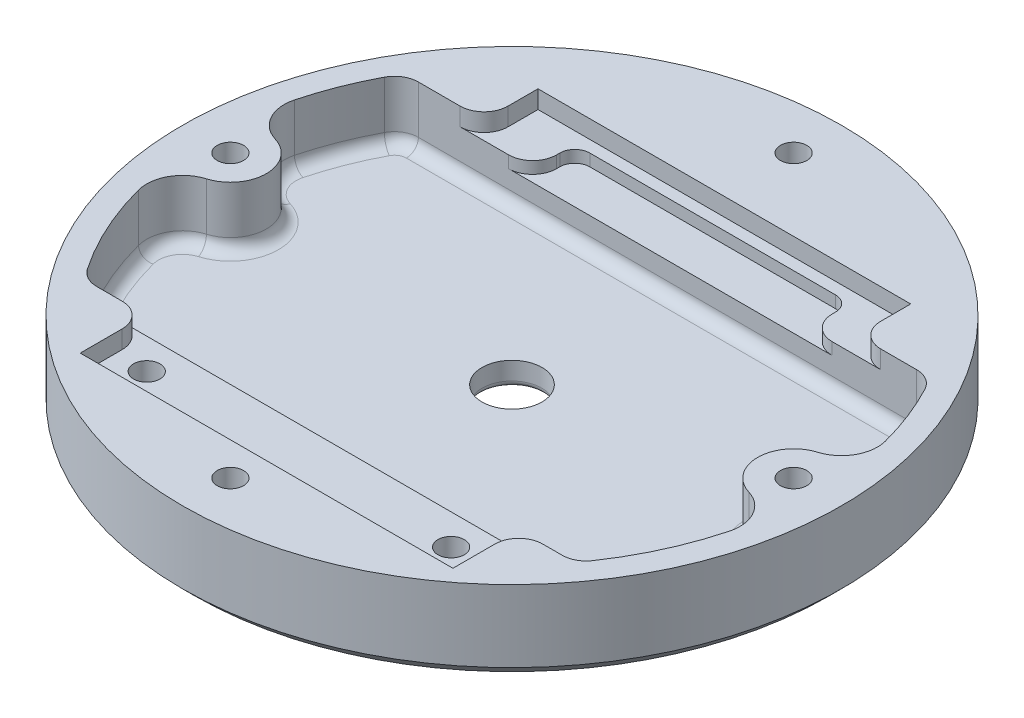
SolidWorks part; units mm, degrees
ref_plane "Спереди" through (0, 0, 0) normal (0, 0, 1) x (1, 0, 0)
ref_plane "Сверху" through (0, 0, 0) normal (0, 1, 0) x (1, 0, 0)
ref_plane "Справа" through (0, 0, 0) normal (1, 0, 0) x (0, 0, -1)
sketch "Эскиз1" plane through (0, 0, 0) normal (0, 1, 0) x (1, 0, 0)
  circle A0 centre (0, 0) radius 27.5
  dimension "D1" = 55
extrude "Бобышка-Вытянуть1" add sketch "Эскиз1" against normal blind 2
sketch "Эскиз2" plane through (0, 0, 0) normal (0, 1, 0) x (1, 0, 0)
  circle A0 centre (0, 0) radius 27.5
  circle A1 centre (0, 0) radius 25.5
  circle A2 centre (0, 0) radius 27.5 construction
  dimension "D1" = 2
extrude "Бобышка-Вытянуть2" add sketch "Эскиз2" along normal blind 5
sketch "Эскиз3" plane through (0, 0, 0) normal (0, 1, 0) x (1, 0, 0)
  line L0 (-21.9552, 12.97) -> (21.9552, 12.97)
  line L1 (15.05, -20.23) -> (-15.05, -20.23) construction
  line L2 (15.05, -20.23) -> (15.05, 16.97) construction
  line L3 (15.05, 16.97) -> (-15.05, 16.97) construction
  line L4 (-15.05, -20.23) -> (-15.05, 16.97) construction
  line L5 (15.05, -20.23) -> (-15.05, 16.97) construction
  line L6 (15.05, 16.97) -> (-15.05, -20.23) construction
  line L7 (-20.4523, -15.23) -> (20.4523, -15.23)
  circle A1 centre (0, 0) radius 25.5
  circle A2 centre (0, 0) radius 25.5 construction
  point P0 (0, -1.63)
  circle M5 centre (0, 0) radius 25.5
  dimension "D1" = 20.23
  dimension "D2" = 37.2
  dimension "D3" = 30.1
  dimension "D4" = 4
  dimension "D5" = 5
extrude "Бобышка-Вытянуть3" add sketch "Эскиз3" along normal up to surface (5 mm away) contours L0 M5 | L7 M5 up to face at (0, 5, 27.5)
sketch "Эскиз6" plane through (0, 5, 0) normal (0, 1, 0) x (1, 0, 0)
  line L1 (-15.3, 17.47) -> (15.8, 17.47)
  line L2 (-15.3, 17.47) -> (-15.3, -20.73)
  line L3 (-15.3, -20.73) -> (15.8, -20.73)
  line L4 (15.8, 17.47) -> (15.8, -20.73)
  line L5 (-15.3, 17.47) -> (15.8, -20.73) construction
  line L6 (-15.3, -20.73) -> (15.8, 17.47) construction
  point P0 (0.25, -1.63)
  point P5 (0, 0)
  dimension "D1" = 20.73
  dimension "D2" = 31.1
  dimension "D3" = 38.2
  dimension "D4" = 0.25
extrude "Вырез-Вытянуть1" cut sketch "Эскиз6" against normal blind 1.5
sketch "Эскиз7" plane through (0, 3.5, 0) normal (0, 1, 0) x (1, 0, 0)
  line L0 (-10, 15.24) -> (10.5, 15.24) construction
  line L1 (-10, 16.49) -> (10.5, 16.49)
  line L2 (-10, 13.99) -> (10.5, 13.99)
  line L3 (15.8, 17.47) -> (-15.3, 17.47) construction
  line L6 (0.25, 17.47) -> (0.25, 12.97) construction
  line L9 (-15.3, 12.97) -> (15.8, 12.97) construction
  line L12 (15.8, 17.47) -> (-15.3, 17.47) construction
  line L13 (-11.25, 15.24) -> (-11.25, 12.97)
  line L14 (-21.9552, 12.97) -> (21.9552, 12.97) construction
  line L15 (-11.25, 12.97) -> (11.75, 12.97)
  line L16 (11.75, 12.97) -> (11.75, 15.24)
  arc A0 (-10, 16.49) -> (-10, 13.99) centre (-10, 15.24) ccw
  arc A1 (10.5, 13.99) -> (10.5, 16.49) centre (10.5, 15.24) ccw
  point P2 (0.25, 15.24)
  line M7 (-15.3, 12.97) -> (15.8, 12.97)
  dimension "D1" = 2.5
  dimension "D2" = 23
  dimension "D3" = 2.23
extrude "Вырез-Вытянуть2" cut sketch "Эскиз7" against normal blind 1 contours L2 A1 L1 A0 | A1 L2 A0 L13 L16 M7
sketch "Эскиз8" plane through (0, 3.5, 0) normal (0, 1, 0) x (1, 0, 0)
  line L0 (0, 0) -> (0, -20.73) construction
  circle A0 centre (-12.7, -17.78) radius 1.1
  circle A1 centre (12.7, -17.78) radius 1.1
  dimension "D3" = 2.2
  dimension "D1" = 17.78
  dimension "D2" = 12.7
extrude "Вырез-Вытянуть3" cut sketch "Эскиз8" against normal through all
sketch "Эскиз9" plane through (0, 5, 0) normal (0, 1, 0) x (1, 0, 0)
  line L0 (0, 23.5) -> (0, -23.5) construction
  line L1 (-23.5, 3) -> (-25.3229, 3)
  line L2 (-23.5, -3) -> (-25.3229, -3)
  line L3 (23.5, 3) -> (25.3229, 3)
  line L4 (23.5, -3) -> (25.3229, -3)
  circle A0 centre (0, 0) radius 23.5 construction
  arc A1 (-23.5, -3) -> (-23.5, 3) centre (-23.5, 0) ccw
  arc A2 (-21.9552, 12.97) -> (-20.4523, -15.23) centre (0, 0) ccw construction
  arc A3 (-21.9552, 12.97) -> (-20.4523, -15.23) centre (0, 0) ccw construction
  arc A4 (-25.3229, -3) -> (-25.3229, 3) centre (0, 0) cw
  arc A5 (23.5, -3) -> (23.5, 3) centre (23.5, 0) cw
  arc A6 (25.3229, -3) -> (25.3229, 3) centre (0, 0) ccw
  point P18 (0, 0)
  dimension "D1" = 47
  dimension "D2" = 6
extrude "Бобышка-Вытянуть4" add sketch "Эскиз9" against normal through all
sketch "Эскиз10" plane through (0, 5, 0) normal (0, 1, 0) x (1, 0, 0)
  circle A0 centre (0, 0) radius 23.5 construction
  circle A1 centre (0, 23.5) radius 1.1
  circle A2 centre (23.5, 0) radius 1.1
  circle A3 centre (0, -23.5) radius 1.1
  circle A4 centre (-23.5, 0) radius 1.1
  point P5 (0, 0)
  point P6 (0, 0)
  dimension "D1" = 47
  dimension "D2" = 2.2
  dimension "D3" = 4
extrude "Вырез-Вытянуть4" cut sketch "Эскиз10" against normal through all
sketch "Эскиз11" plane through (0, -2, 0) normal (0, -1, 0) x (1, 0, 0)
  line L0 (0, 0) -> (0, 23.5) construction
  line L1 (1.1258, 21.55) -> (2.2517, 23.5)
  line L2 (2.2517, 23.5) -> (1.1258, 25.45)
  line L3 (1.1258, 25.45) -> (-1.1258, 25.45)
  line L4 (-1.1258, 25.45) -> (-2.2517, 23.5)
  line L5 (-2.2517, 23.5) -> (-1.1258, 21.55)
  line L6 (-1.1258, 21.55) -> (1.1258, 21.55)
  line L7 (13.8258, 15.83) -> (14.9517, 17.78)
  line L8 (14.9517, 17.78) -> (13.8258, 19.73)
  line L9 (13.8258, 19.73) -> (11.5742, 19.73)
  line L10 (11.5742, 19.73) -> (10.4483, 17.78)
  line L11 (10.4483, 17.78) -> (11.5742, 15.83)
  line L12 (11.5742, 15.83) -> (13.8258, 15.83)
  line L13 (-11.5742, 15.83) -> (-13.8258, 15.83)
  line L14 (-10.4483, 17.78) -> (-11.5742, 15.83)
  line L15 (-11.5742, 19.73) -> (-10.4483, 17.78)
  line L16 (-13.8258, 19.73) -> (-11.5742, 19.73)
  line L17 (-14.9517, 17.78) -> (-13.8258, 19.73)
  line L18 (-13.8258, 15.83) -> (-14.9517, 17.78)
  line L19 (21.55, -1.1258) -> (23.5, -2.2517)
  line L20 (23.5, -2.2517) -> (25.45, -1.1258)
  line L21 (25.45, -1.1258) -> (25.45, 1.1258)
  line L22 (25.45, 1.1258) -> (23.5, 2.2517)
  line L23 (23.5, 2.2517) -> (21.55, 1.1258)
  line L24 (21.55, 1.1258) -> (21.55, -1.1258)
  line L25 (-1.1258, -21.55) -> (-2.2517, -23.5)
  line L26 (-2.2517, -23.5) -> (-1.1258, -25.45)
  line L27 (-1.1258, -25.45) -> (1.1258, -25.45)
  line L28 (1.1258, -25.45) -> (2.2517, -23.5)
  line L29 (2.2517, -23.5) -> (1.1258, -21.55)
  line L30 (1.1258, -21.55) -> (-1.1258, -21.55)
  line L31 (-21.55, 1.1258) -> (-23.5, 2.2517)
  line L32 (-23.5, 2.2517) -> (-25.45, 1.1258)
  line L33 (-25.45, 1.1258) -> (-25.45, -1.1258)
  line L34 (-25.45, -1.1258) -> (-23.5, -2.2517)
  line L35 (-23.5, -2.2517) -> (-21.55, -1.1258)
  line L36 (-21.55, -1.1258) -> (-21.55, 1.1258)
  circle A0 centre (0, 23.5) radius 1.95 construction
  circle A1 centre (12.7, 17.78) radius 1.95 construction
  circle A2 centre (-12.7, 17.78) radius 1.95 construction
  circle A3 centre (23.5, 0) radius 1.95 construction
  circle A4 centre (0, -23.5) radius 1.95 construction
  circle A5 centre (-23.5, 0) radius 1.95 construction
  circle A6 centre (23.5, 0) radius 1.1 construction
  point P10 (0, 25.45)
  dimension "D3" = 4
  dimension "D1" = 3.9
  dimension "D2" = 3.9
extrude "Вырез-Вытянуть5" cut sketch "Эскиз11" against normal blind 2.2
fillet "Скругление1" radius 2 10 edges at (20.4523, 2.5, 15.23) (-20.4523, 2.5, 15.23) (-21.9552, 2.5, -12.97) (21.9552, 2.5, -12.97) (15.8, 4.25, -12.97) (-15.3, 4.25, -12.97) (-11.25, 3, -12.97) (11.75, 3, -12.97) (-15.3, 4.25, 15.23) (15.8, 4.25, 15.23)
fillet "Скругление2" radius 3 4 edges at (-25.3229, 2.5, -3) (-25.3229, 2.5, 3) (25.3229, 2.5, 3) (25.3229, 2.5, -3)
chamfer "Фаска1" distance 1 angle 45 1 edges at (0, -2, 27.5)
sketch "Эскиз13" plane through (0, 0, 0) normal (0, 1, 0) x (1, 0, 0)
  circle A0 centre (0, 0) radius 2.5
  dimension "D1" = 5
extrude "Вырез-Вытянуть6" cut sketch "Эскиз13" against normal through all
fillet "Скругление3" radius 0.5 1 edges at (0, -2, 2.5)
fillet "Скругление4" radius 1 16 edges at (23.7574, 0, -9.2649) (24.3752, 0, -4.2791) (20.5, 0, 0) (24.3752, 0, 4.2791) (23.1999, 0, 10.5836) (20.357, 0, 14.998) (0, 0, 15.23) (-20.357, 0, 14.998) (-23.1999, 0, 10.5836) (-24.3752, 0, 4.2791) (-20.5, 0, 0) (-24.3752, 0, -4.2791) (-23.7574, 0, -9.2649) (-21.8151, 0, -12.6828) (0, 0, -12.97) (21.8151, 0, -12.6828)
equation "\"sensor_d\" = 55"
equation "\"sensor_thikness\"= 2"
equation "\"screw_d\"= 2"
equation "\"screw_h1\"= 12"
equation "\"screw_h2\"= 8"
equation "\"screw_hh_d\"= 3.8"
equation "\"screw_hh_h\"= 2"
equation "\"print_offset\"= 0.2"
equation "\"nut_d\"= 3.8"
equation "\"nut_h\"= 2"
equation "\"mounting_r\"= \"sensor_d\" - 8"
equation "\"D1@Эскиз1\"=\"sensor_d\""
equation "\"D1@Бобышка-Вытянуть1\"= \"sensor_thikness\""
equation "\"D1@Эскиз2\" = \"sensor_thikness\""
equation "\"board_size_a\"= 37.2"
equation "\"board_size_b\"= 30.1"
equation "\"mount_hole_a\"= 12.7"
equation "\"mount_hole_b\"= 17.78"
equation "\"D2@Эскиз3\"=\"board_size_a\""
equation "\"D3@Эскиз3\"=\"board_size_b\""
equation "\"D5@Эскиз3\"=5"
equation "\"board_size_c\"= 20.23"
equation "\"D1@Эскиз3\"=\"board_size_c\""
equation "\"D1@Эскиз6\"=\"board_size_c\"+0.5"
equation "\"D2@Эскиз6\"=\"board_size_b\"+1"
equation "\"D3@Эскиз6\"=\"board_size_a\"+1"
equation "\"D1@Вырез-Вытянуть1\"=1.50мм"
equation "\"D1@Эскиз8\"=\"mount_hole_b\""
equation "\"D2@Эскиз8\"=\"mount_hole_a\""
equation "\"D3@Эскиз8\"=\"screw_d\"+\"print_offset\""
equation "\"board_size_d\"= 0.25"
equation "\"D4@Эскиз6\"=\"board_size_d\""
equation "\"D1@Эскиз9\"=\"mounting_r\""
equation "\"D2@Эскиз9\"=\"screw_d\"*3"
equation "\"D1@Эскиз10\"=\"mounting_r\""
equation "\"D2@Эскиз10\"=\"screw_d\"+\"print_offset\""
equation "\"D1@Эскиз11\"=\"nut_d\"+\"print_offset\"/2"
equation "\"D2@Эскиз11\"=\"D1@Эскиз11\""
equation "\"D1@Вырез-Вытянуть5\"=\"nut_h\"+\"print_offset\""
